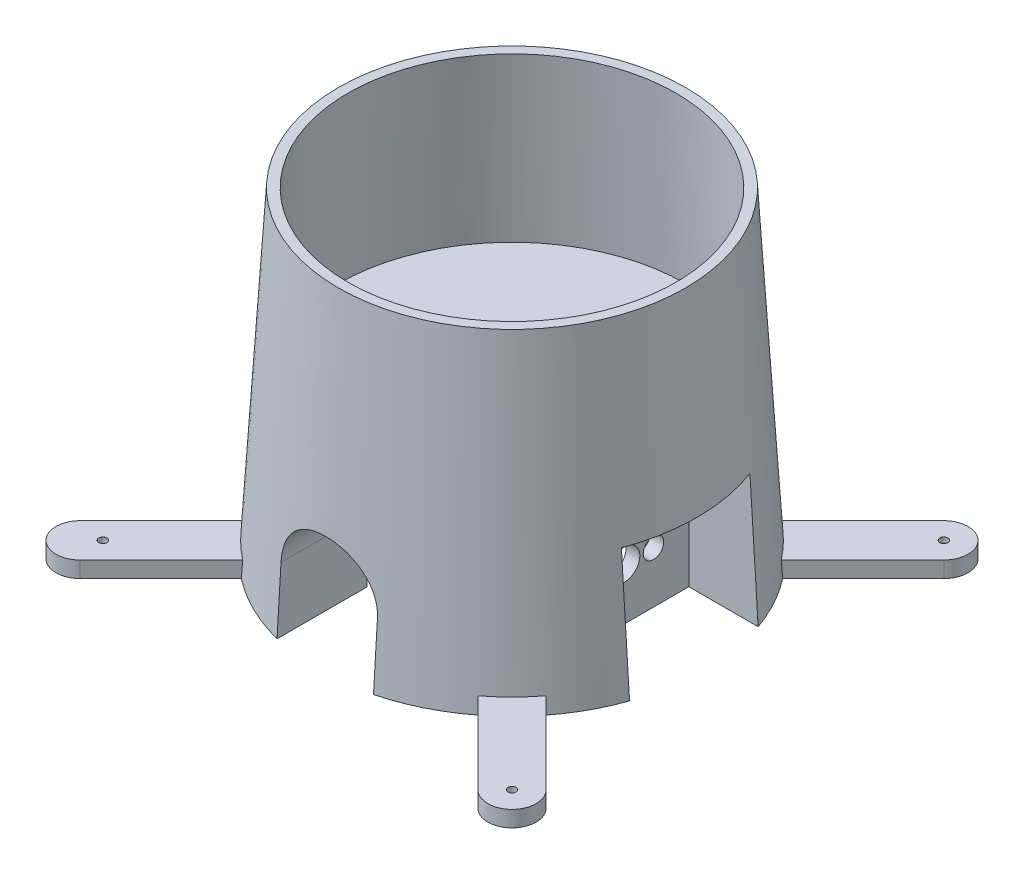
SolidWorks part; units mm, degrees
ref_plane "前视基准面" through (0, 0, 0) normal (0, 0, 1) x (1, 0, 0)
ref_plane "上视基准面" through (0, 0, 0) normal (0, 1, 0) x (1, 0, 0)
ref_plane "右视基准面" through (0, 0, 0) normal (1, 0, 0) x (0, 0, -1)
sketch "草图3" plane through (0, 0, 0) normal (1, 0, 0) x (0, 0, -1)
  line L0 (0, 0) -> (60, 0)
  line L1 (60, 0) -> (54, 100)
  line L2 (54, 100) -> (0, 100)
  line L3 (0, 100) -> (0, 0)
  dimension "D1" = 100
  dimension "D2" = 54
  dimension "D3" = 60
revolve "旋转2" add sketch "草图3" angle 360 about L3
sketch "草图5" plane through (0, 0, 0) normal (0, -1, 0) x (-1, 0, 0)
  line L0 (0, 0) -> (0, 71.9204) construction
  line L1 (0, 0) -> (72.7838, 0) construction
  line L3 (30.75, -30.1) -> (-30.75, -30.1)
  line L4 (30.75, -30.1) -> (30.75, 30.1)
  line L5 (30.75, 30.1) -> (-30.75, 30.1)
  line L6 (-30.75, -30.1) -> (-30.75, 30.1)
  dimension "D1" = 60.2
  dimension "D2" = 61.5
extrude "切除-拉伸1" cut sketch "草图5" against normal blind 40
sketch "草图6" plane through (0, 0, 0) normal (1, 0, 0) x (0, 0, -1)
  line L0 (0, 0) -> (0, 62.3248) construction
  line L1 (-60, 0) -> (60, 0) construction
  line L2 (-20, 0) -> (20, 0)
  line L3 (-20, 0) -> (-20, 40)
  line L4 (-20, 40) -> (20, 40)
  line L5 (20, 0) -> (20, 40)
  dimension "D1" = 40
  dimension "D2" = 40
extrude "切除-拉伸2" cut sketch "草图6" against normal blind 35 from offset 35 offset against normal yes
sketch "草图9" plane through (0, 0, 0) normal (1, 0, 0) x (0, 0, -1)
  line L0 (0, 0) -> (0, 62.3248) construction
  line L2 (-20, 0) -> (20, 0)
  line L3 (-20, 0) -> (-20, 40)
  line L4 (-20, 40) -> (20, 40)
  line L5 (20, 0) -> (20, 40)
  dimension "D1" = 40
  dimension "D2" = 40
extrude "切除-拉伸3" cut sketch "草图9" along normal blind 40 from offset 35
sketch "草图10" plane through (0, 0, 30.1) normal (0, 0, -1) x (-1, 0, 0)
  line L0 (0, 0) -> (0, 41.5034) construction
  line L1 (-15, 0) -> (-15, 20)
  line L2 (-56.5685, 0) -> (56.5685, 0) construction
  line L3 (-15, 0) -> (15, 0)
  line L4 (15, 0) -> (15, 20)
  arc A0 (-15, 20) -> (15, 20) centre (0, 20) cw
  dimension "D3" = 15
  dimension "D1" = 15
  dimension "D2" = 20
extrude "切除-拉伸4" cut sketch "草图10" against normal blind 40
sketch "草图11" plane through (0, 0, 0) normal (0, 0, 1) x (1, 0, 0)
  line L0 (-50.9946, 100) -> (-54.1746, 47)
  line L1 (54, 100) -> (-54, 100) construction
  line L2 (-54.1746, 47) -> (0, 47)
  line L3 (0, 47) -> (0, 100)
  line L4 (0, 100) -> (-50.9946, 100)
  line L5 (-54, 100) -> (-57.6, 40) construction
  dimension "D1" = 53
  dimension "D2" = 3
revolve "切除-旋转1" cut sketch "草图11" angle 360 about L3
hole_wizard "Ø2.5mm 暗销孔1" positions "草图14" profile "草图15" hole size "Ø2.5" standard "ISO" end condition through all
sketch "草图14" plane through (0, 47, 0) normal (0, 1, 0) x (1, 0, 0)
  line L0 (0, 0) -> (97.1322, 0) construction
  line L2 (0, 0) -> (0, -66.7943) construction
  point P17 (-10.5, 13.5)
  point P21 (-10.5, -13.5)
  point P22 (41.5, 13.5)
  point P32 (41.5, -13.5)
  dimension "D1" = 13.5
  dimension "D2" = 10.5
  dimension "D3" = 52
  dimension "D4" = 13.5
sketch "草图15" plane through (41.5, 47, 13.5) normal (1, 0, 0) x (0, 0, 1)
  line L0 (0, 0) -> (0, 47)
  line L1 (0, 47) -> (1.25, 47)
  line L2 (1.25, 47) -> (1.25, 0.025)
  line L3 (1.25, 0.025) -> (1.275, 0)
  line L5 (1.275, 0) -> (0, 0)
  line L6 (-1.25, 0.025) -> (-1.275, 0) construction
  line L11 (0, -6.35) -> (0, 107.95) construction
  dimension "通孔孔直径" = 2.5
  dimension "通孔孔深度" = 47
  dimension "近端锥形沉头孔直径" = 2.55
  dimension "近端锥形沉头孔角度" = 90
sketch "草图16" plane through (0, 0, -30.1) normal (0, 0, 1) x (1, 0, 0)
  line L0 (15, 20) -> (15, 0) construction
  line L1 (-15, 0) -> (-15, 20) construction
  line L2 (15, 20) -> (15, 0)
  line L3 (-15, 0) -> (-15, 20)
  line L4 (15, 0) -> (-15, 0)
  arc A0 (15, 20) -> (-15, 20) centre (0, 20) ccw construction
  arc A1 (15, 20) -> (-15, 20) centre (0, 20) ccw
extrude "切除-拉伸5" cut sketch "草图16" against normal blind 10
hole_wizard "3/8 (0.375) 直径孔1" positions "草图17" profile "草图18" hole size "3/8" standard "ANSI Inch" end condition through all
sketch "草图17" plane through (-35, 0, 0) normal (-1, 0, 0) x (0, 0, 1)
  point P0 (0, 16)
  dimension "D1" = 16
sketch "草图18" plane through (-35, 16, 0) normal (0, 1, 0) x (0, 0, 1)
  line L0 (0, 0) -> (0, 92.6)
  line L1 (0, 92.6) -> (4.7625, 92.6)
  line L2 (4.7625, 92.6) -> (4.7625, 0.635)
  line L3 (4.7625, 0.635) -> (5.3975, 0)
  line L5 (5.3975, 0) -> (0, 0)
  line L6 (-4.7625, 0.635) -> (-5.3975, 0) construction
  line L11 (0, -6.35) -> (0, 107.95) construction
  dimension "通孔孔直径" = 9.525
  dimension "通孔孔深度" = 92.6
  dimension "近端锥形沉头孔直径" = 10.795
  dimension "近端锥形沉头孔角度" = 90
hole_wizard "1/4 (0.25) 直径孔1" positions "草图19" profile "草图20" hole size "1/4" standard "ANSI Inch" end condition through all
sketch "草图19" plane through (-35, 0, 0) normal (-1, 0, 0) x (0, 0, 1)
  line L0 (0, 16) -> (0, 1.7388) construction
  line L2 (-0.701, 16) -> (-13.7276, 16) construction
  circle A0 centre (0, 16) radius 4.7625 construction
  point P15 (-9, 16)
  point P20 (9, 16)
  dimension "D1" = 9
sketch "草图20" plane through (-35, 16, 9) normal (0, 1, 0) x (0, 0, 1)
  line L0 (0, 0) -> (0, 92.6)
  line L1 (0, 92.6) -> (3.175, 92.6)
  line L2 (3.175, 92.6) -> (3.175, 0.635)
  line L3 (3.175, 0.635) -> (3.81, 0)
  line L5 (3.81, 0) -> (0, 0)
  line L6 (-3.175, 0.635) -> (-3.81, 0) construction
  line L11 (0, -6.35) -> (0, 107.95) construction
  dimension "通孔孔直径" = 6.35
  dimension "通孔孔深度" = 92.6
  dimension "近端锥形沉头孔直径" = 7.62
  dimension "近端锥形沉头孔角度" = 90
sketch "草图21" plane through (0, 0, 0) normal (0, -1, 0) x (1, 0, 0)
  line L0 (0, 0) -> (93.8476, 0) construction
  line L1 (0, 0) -> (0, 95.018) construction
  line L2 (0, 0) -> (52.9095, 52.9095) construction
  line L12 (0, 0) -> (51.0353, -51.0353) construction
  line L14 (-40.6586, 30.052) -> (-72.4784, 61.8718)
  line L27 (-40.6586, 30.052) -> (-30.052, 40.6586)
  line L29 (-30.052, 40.6586) -> (-61.8718, 72.4784)
  line L30 (40.6586, 30.052) -> (72.4784, 61.8718)
  line L31 (30.052, 40.6586) -> (61.8718, 72.4784)
  line L39 (30.052, 40.6586) -> (40.6586, 30.052)
  line L40 (30.052, -40.6586) -> (61.8718, -72.4784)
  line L41 (40.6586, -30.052) -> (72.4784, -61.8718)
  line L42 (40.6586, -30.052) -> (30.052, -40.6586)
  line L43 (-40.6586, -30.052) -> (-72.4784, -61.8718)
  line L44 (-30.052, -40.6586) -> (-61.8718, -72.4784)
  line L45 (-30.052, -40.6586) -> (-40.6586, -30.052)
  arc A5 (-72.4784, 61.8718) -> (-61.8718, 72.4784) centre (-67.1751, 67.1751) cw
  arc A6 (61.8718, 72.4784) -> (72.4784, 61.8718) centre (67.1751, 67.1751) cw
  arc A7 (72.4784, -61.8718) -> (61.8718, -72.4784) centre (67.1751, -67.1751) cw
  arc A8 (-61.8718, -72.4784) -> (-72.4784, -61.8718) centre (-67.1751, -67.1751) cw
  dimension "D2" = 50
  dimension "D3" = 95
  dimension "D1" = 15
  dimension "D4" = 4
extrude "凸台-拉伸1" add sketch "草图21" against normal blind 5
hole_wizard "Ø2.5mm 暗销孔2" positions "草图23" profile "草图24" hole size "Ø2.5" standard "ISO" end condition through all
sketch "草图23" plane through (0, 5, 0) normal (0, 1, 0) x (1, 0, 0)
  point P4 (-67.1751, 67.1751)
  point P7 (67.1751, 67.1751)
  point P10 (67.1751, -67.1751)
  point P13 (-63.6396, -63.6396)
sketch "草图24" plane through (-67.1751, 5, -67.1751) normal (1, 0, 0) x (0, 0, 1)
  line L0 (0, 0) -> (0, 5)
  line L1 (0, 5) -> (1.25, 5)
  line L2 (1.25, 5) -> (1.25, 0.025)
  line L3 (1.25, 0.025) -> (1.275, 0)
  line L5 (1.275, 0) -> (0, 0)
  line L6 (-1.25, 0.025) -> (-1.275, 0) construction
  line L11 (0, -6.35) -> (0, 107.95) construction
  dimension "通孔孔直径" = 2.5
  dimension "通孔孔深度" = 5
  dimension "近端锥形沉头孔直径" = 2.55
  dimension "近端锥形沉头孔角度" = 90
